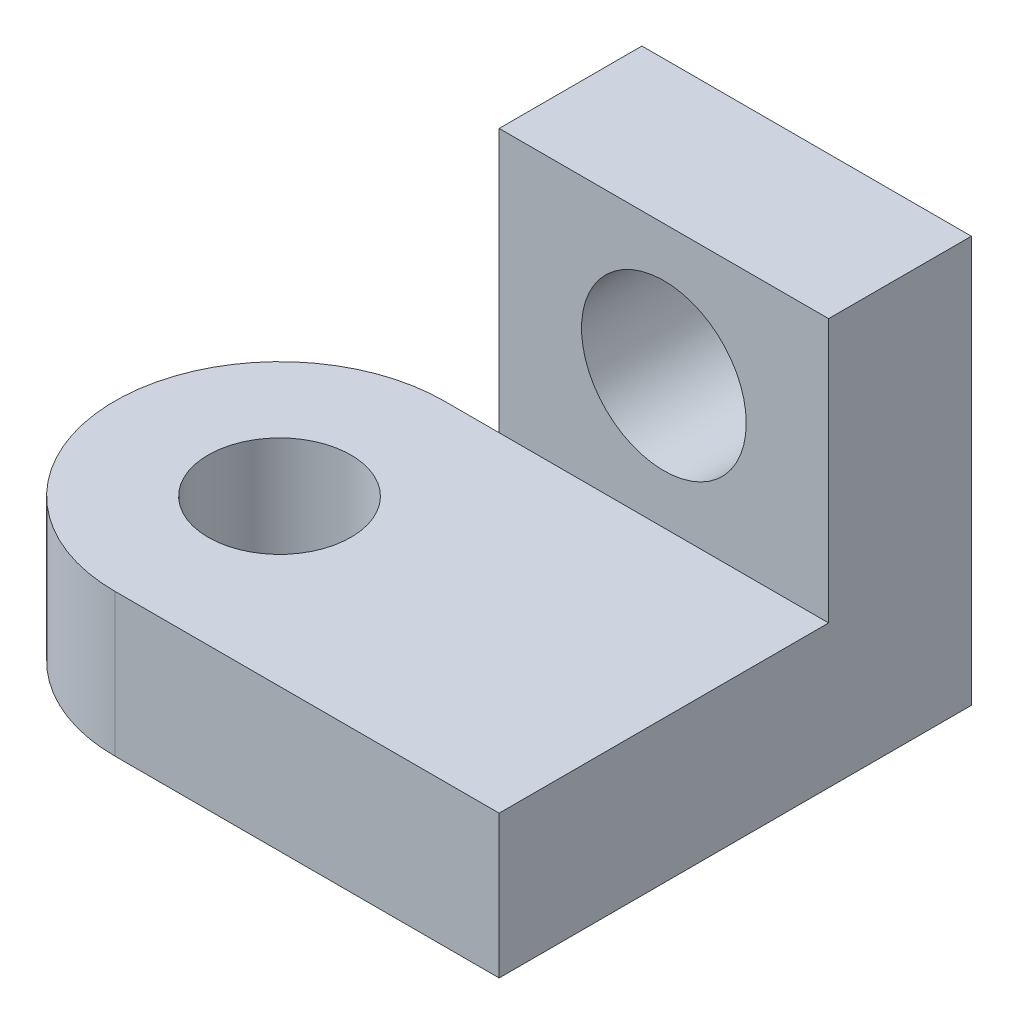
SolidWorks part; units mm, degrees
ref_plane "Front Plane" through (0, 0, 0) normal (0, 0, 1) x (1, 0, 0)
ref_plane "Top Plane" through (0, 0, 0) normal (0, 1, 0) x (1, 0, 0)
ref_plane "Right Plane" through (0, 0, 0) normal (1, 0, 0) x (0, 0, -1)
sketch "Sketch2" plane through (0, 0, 0) normal (1, 0, 0) x (0, 0, -1)
  line L0 (0, 0) -> (0, 37)
  line L1 (0, 37) -> (-13, 37)
  line L2 (-13, 37) -> (-13, 13)
  line L3 (-13, 13) -> (-43, 13)
  line L4 (0, 0) -> (-43, 0)
  line L5 (-43, 13) -> (-43, 0)
  dimension "D1" = 13
  dimension "D2" = 43
  dimension "D3" = 24
  dimension "D4" = 30
extrude "Boss-Extrude3" add sketch "Sketch2" along normal blind 30
sketch "Sketch4" plane through (0, 13, 0) normal (0, 1, 0) x (1, 0, 0)
  line L0 (0, -13) -> (0, -43)
  line L1 (0, -43) -> (-5, -43)
  line L2 (-5, -13) -> (0, -13)
  arc A0 (-5, -43) -> (-5, -13) centre (-5, -28) cw
  circle A3 centre (-5, -28) radius 6.5
  dimension "D2" = 13
  dimension "D1" = 5
extrude "Boss-Extrude5" add sketch "Sketch4" against normal blind 13 contours A0 L2 L0 L1
sketch "Sketch6" plane through (0, 13, 0) normal (0, 1, 0) x (1, 0, 0)
  circle A0 centre (-5, -28) radius 6.5
  dimension "D1" = 13
extrude "Cut-Extrude1" cut sketch "Sketch6" against normal blind 13
sketch "Sketch7" plane through (0, 0, 13) normal (0, 0, 1) x (1, 0, 0)
  line L0 (30, 37) -> (0, 37) construction
  line L2 (0, 37) -> (0, 13) construction
  circle A0 centre (15, 25) radius 7.5
  dimension "D1" = 15
  dimension "D2" = 12
  dimension "D3" = 15
extrude "Cut-Extrude2" cut sketch "Sketch7" against normal blind 13
